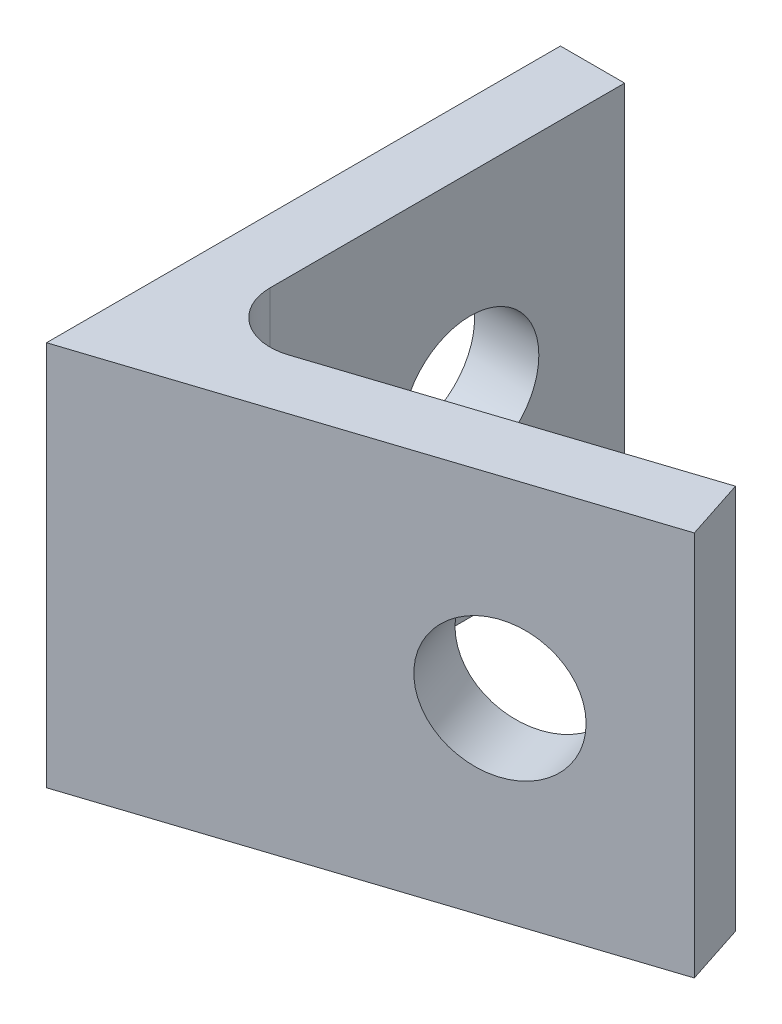
SolidWorks part; units mm, degrees
material "ABS"
ref_plane "Front" through (0, 0, 0) normal (0, 0, 1) x (1, 0, 0)
ref_plane "Top" through (0, 0, 0) normal (0, 1, 0) x (1, 0, 0)
ref_plane "Right" through (0, 0, 0) normal (1, 0, 0) x (0, 0, -1)
sketch "Sketch1" plane through (0, 0, 0) normal (0, 1, 0) x (1, 0, 0)
  line L0 (0, 0) -> (0, 25.4)
  line L1 (0, -50) -> (0, 50) construction
  line L2 (0, 25.4) -> (3.175, 25.4)
  line L3 (3.175, 25.4) -> (3.175, 4.3733)
  line L4 (3.175, 4.3733) -> (23.1678, 10.8854)
  line L5 (23.1678, 10.8854) -> (24.1511, 7.8665)
  line L6 (24.1511, 7.8665) -> (0, 0)
  line L7 (3.175, 4.3733) -> (3.175, 80.5733) construction
  line L8 (3.175, 80.5733) -> (86.375, 53.4733) construction
  line L9 (86.375, 53.4733) -> (86.375, 31.4733) construction
  line L10 (86.375, 31.4733) -> (3.175, 4.3733) construction
  point P6 (80.9625, 17.8341)
  dimension "D1" = 25.4
  dimension "D2" = 3.175
  dimension "D3" = 76.2
  dimension "D4" = 83.2
  dimension "D5" = 22
extrude "Boss-Extrude1" add sketch "Sketch1" along normal blind 19.05 contours L4 L5 L6 L0 L2 L3
fillet "Fillet1" radius 2.54 1 edges at (3.175, 9.525, -4.3733)
hole_wizard "1/4 Clearance Hole1" positions "Sketch3" profile "Sketch4" hole size "1/4" standard "ANSI Inch" end condition up to next
sketch "Sketch3" plane through (0, 0, 0) normal (-1, 0, 0) x (0, 0, 1)
  line L0 (-17.78, 19.05) -> (-17.78, 0) construction
  line L1 (0, 19.05) -> (-25.4, 19.05) construction
  line L2 (50, 0) -> (-50, 0) construction
  line L4 (0, -50) -> (0, 50) construction
  point P0 (-17.78, 9.525)
  dimension "D1" = 17.78
sketch "Sketch4" plane through (0, 9.525, -17.78) normal (0, 1, 0) x (0, 0, 1)
  line L0 (0, 0) -> (0, 3.175)
  line L1 (0, 3.175) -> (3.3782, 3.175)
  line L2 (3.3782, 3.175) -> (3.3782, 0)
  line L5 (3.3782, 0) -> (0, 0)
  line L11 (0, -6.35) -> (0, 107.95) construction
  dimension "Thru Hole Dia." = 6.7564
  dimension "Thru Hole Depth" = 3.175
hole_wizard "1/4 Clearance Hole2" positions "Sketch5" profile "Sketch6" hole size "1/4" standard "ANSI Inch" end condition up to next
sketch "Sketch5" plane through (0, 0, 0) normal (0.3097, 0, 0.9508) x (0.9508, 0, -0.3097)
  line L0 (17.78, 19.05) -> (17.78, 0) construction
  line L1 (25.4, 19.05) -> (0, 19.05) construction
  line L2 (50, 0) -> (-50, 0) construction
  line L4 (0, 19.05) -> (0, 0) construction
  point P0 (17.78, 9.525)
  point P11 (0, 0)
  dimension "D1" = 17.78
sketch "Sketch6" plane through (16.9058, 9.525, -5.5066) normal (0, 1, 0) x (0.9508, 0, -0.3097)
  line L0 (0, 0) -> (0, 3.175)
  line L1 (0, 3.175) -> (3.3782, 3.175)
  line L2 (3.3782, 3.175) -> (3.3782, 0)
  line L5 (3.3782, 0) -> (0, 0)
  line L11 (0, -6.35) -> (0, 107.95) construction
  dimension "Thru Hole Dia." = 6.7564
  dimension "Thru Hole Depth" = 3.175
